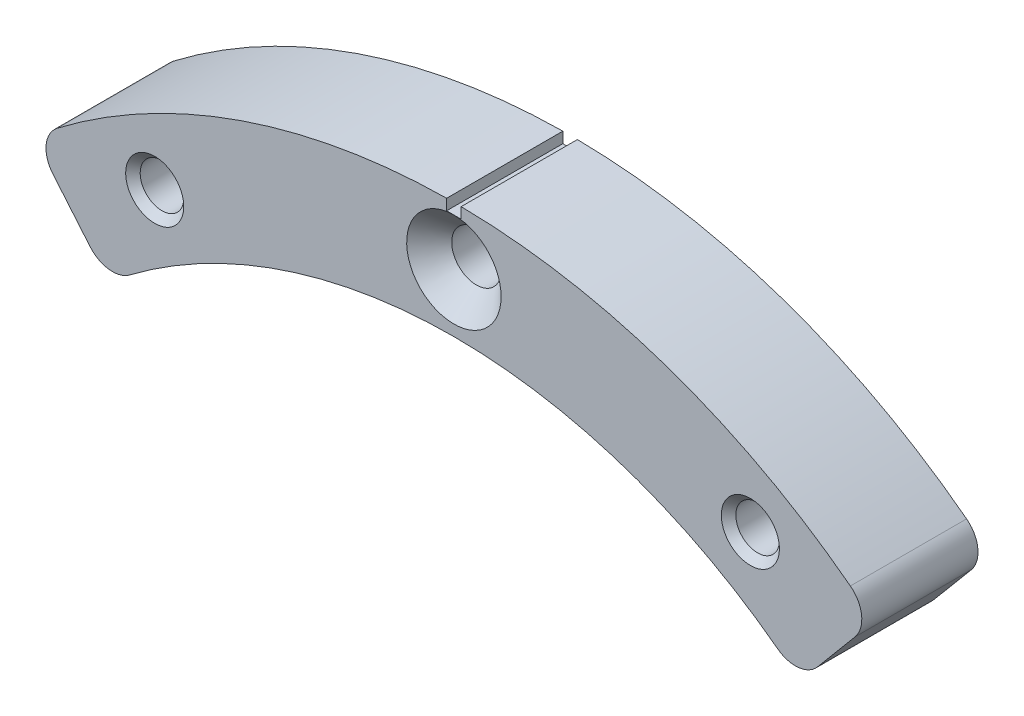
SolidWorks part; units mm, degrees
material "45#"
ref_plane "前视基准面" through (0, 0, 0) normal (0, 0, 1) x (1, 0, 0)
ref_plane "上视基准面" through (0, 0, 0) normal (0, 1, 0) x (1, 0, 0)
ref_plane "右视基准面" through (0, 0, 0) normal (1, 0, 0) x (0, 0, -1)
sketch "草图1" plane through (0, 0, 0) normal (0, 0, 1) x (1, 0, 0)
  line L0 (-26.3543, 31.4078) -> (0, 0) construction
  line L1 (0, 0) -> (26.3543, 31.4078) construction
  line L2 (0, 0) -> (0, 71.2871) construction
  line L3 (-28.9254, 34.472) -> (-23.7831, 28.3436)
  line L4 (23.7831, 28.3436) -> (28.9254, 34.472)
  arc A0 (-26.3543, 31.4078) -> (26.3543, 31.4078) centre (0, 0) cw construction
  arc A1 (-23.7831, 28.3436) -> (23.7831, 28.3436) centre (0, 0) cw
  arc A2 (-28.9254, 34.472) -> (28.9254, 34.472) centre (0, 0) cw
  dimension "D1" = 41
  dimension "D2" = 40
  dimension "D3" = 40
  dimension "D4" = 4
  dimension "D5" = 4
extrude "凸台-拉伸1" add sketch "草图1" along normal blind 8
hole_wizard "打孔尺寸(%根据)内六角花形半沉头螺钉的类型1" positions "草图3" profile "草图4" countersink size "M6" standard "GB"
sketch "草图3" plane through (0, 0, 8) normal (0, 0, 1) x (1, 0, 0)
  line L0 (0, 0) -> (0, 41)
  line L2 (0, 0) -> (-20.5, 35.507)
  line L4 (0, 0) -> (20.5, 35.507)
  circle A0 centre (0, 0) radius 41 construction
  point P4 (0, 41)
  dimension "D3" = 82
  dimension "D1" = 30
  dimension "D2" = 30
sketch "草图4" plane through (0, 41, 8) normal (1, 0, 0) x (0, -1, 0)
  line L0 (0, 0) -> (0, 11.0215)
  line L1 (0, 11.0215) -> (1.7, 10)
  line L2 (1.7, 10) -> (1.7, 1.55)
  line L3 (1.7, 1.55) -> (3.25, 0)
  line L5 (3.25, 0) -> (0, 0)
  line L6 (-1.7, 1.55) -> (-3.25, 0) construction
  line L10 (0, 11.0215) -> (-1.7, 10) construction
  line L11 (0, -6.35) -> (0, 107.95) construction
  dimension "孔直径" = 3.4
  dimension "孔深度" = 10
  dimension "近端锥形沉头孔直径" = 6.5
  dimension "近端锥形沉头孔角度" = 90
  dimension "导头角度" = 118
fillet "圆角1" radius 2 4 edges at (-23.7831, 28.3436, 4) (-28.9254, 34.472, 4) (28.9254, 34.472, 4) (23.7831, 28.3436, 4)
hole_wizard "大小mm 暗销孔2" positions "草图5" profile "草图6" hole size "Ø3.0" standard "GB" end condition through all
sketch "草图5" plane through (0, 0, 8) normal (0, 0, 1) x (1, 0, 0)
  line L0 (0, 0) -> (0, 41) construction
  line L2 (0, 0) -> (-20.5929, 35.4533) construction
  line L4 (0, 0) -> (20.407, 35.5606) construction
  point P8 (-20.5929, 35.4533)
  point P11 (20.407, 35.5606)
  dimension "D1" = 30.15
  dimension "D2" = 41
  dimension "D3" = 29.85
sketch "草图6" plane through (20.407, 35.5606, 8) normal (1, 0, 0) x (0, -1, 0)
  line L0 (0, 0) -> (0, 8)
  line L1 (0, 8) -> (1.5, 8)
  line L2 (1.5, 8) -> (1.5, 0)
  line L5 (1.5, 0) -> (0, 0)
  line L11 (0, -6.35) -> (0, 107.95) construction
  dimension "通孔孔直径" = 3
  dimension "通孔孔深度" = 8
chamfer "倒角1" distance 0.5 angle 45 2 edges at (21.907, 35.5606, 8) (-19.0929, 35.4533, 8)
sketch "草图7" plane through (0, 0, 8) normal (0, 0, 1) x (1, 0, 0)
  line L1 (-0.5, 45.75) -> (0.5, 45.75)
  line L2 (-0.5, 45.75) -> (-0.5, 44.25)
  line L3 (-0.5, 44.25) -> (0.5, 44.25)
  line L4 (0.5, 45.75) -> (0.5, 44.25)
  line L5 (-0.5, 45.75) -> (0.5, 44.25) construction
  line L6 (-0.5, 44.25) -> (0.5, 45.75) construction
  arc A0 (27.2908, 35.7801) -> (-27.2908, 35.7801) centre (0, 0) ccw construction
  point P0 (0, 45)
  dimension "D1" = 1
  dimension "D2" = 1.5
extrude "切除-拉伸1" cut sketch "草图7" against normal through all
equation "\"D3@草图1\"=\"D2@草图1\""
